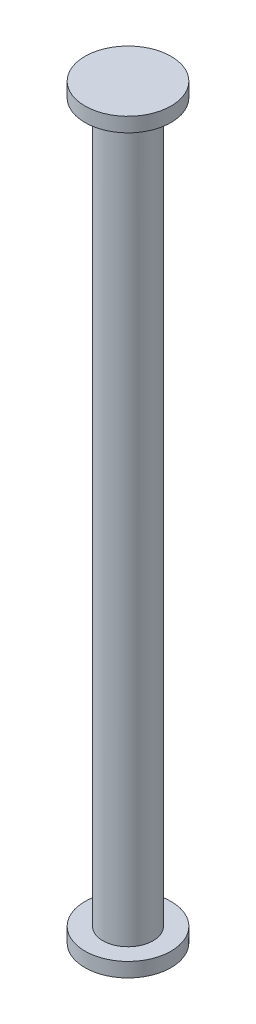
SolidWorks part; units mm, degrees
material "Cast Alloy Steel"
ref_plane "Front Plane" through (0, 0, 0) normal (0, 0, 1) x (1, 0, 0)
ref_plane "Top Plane" through (0, 0, 0) normal (0, 1, 0) x (1, 0, 0)
ref_plane "Right Plane" through (0, 0, 0) normal (1, 0, 0) x (0, 0, -1)
sketch "Sketch1" plane through (0, 0, 0) normal (0, 1, 0) x (1, 0, 0)
  circle A0 centre (0, 0) radius 4.445
  dimension "D1" = 8.89
extrude "Boss-Extrude1" add sketch "Sketch1" along normal blind 127
sketch "Sketch2" plane through (0, 0, 0) normal (0, -1, 0) x (1, 0, 0)
  circle A0 centre (0, 0) radius 7.62
  dimension "D2" = 15.24
sketch "Sketch3" plane through (0, 127, 0) normal (0, 1, 0) x (1, 0, 0)
  circle A0 centre (0, 0) radius 7.62
  dimension "D2" = 15.24
extrude "Boss-Extrude2" add sketch "Sketch2" along normal blind 2.54
extrude "Boss-Extrude3" add sketch "Sketch3" along normal blind 2.54 contours A0
